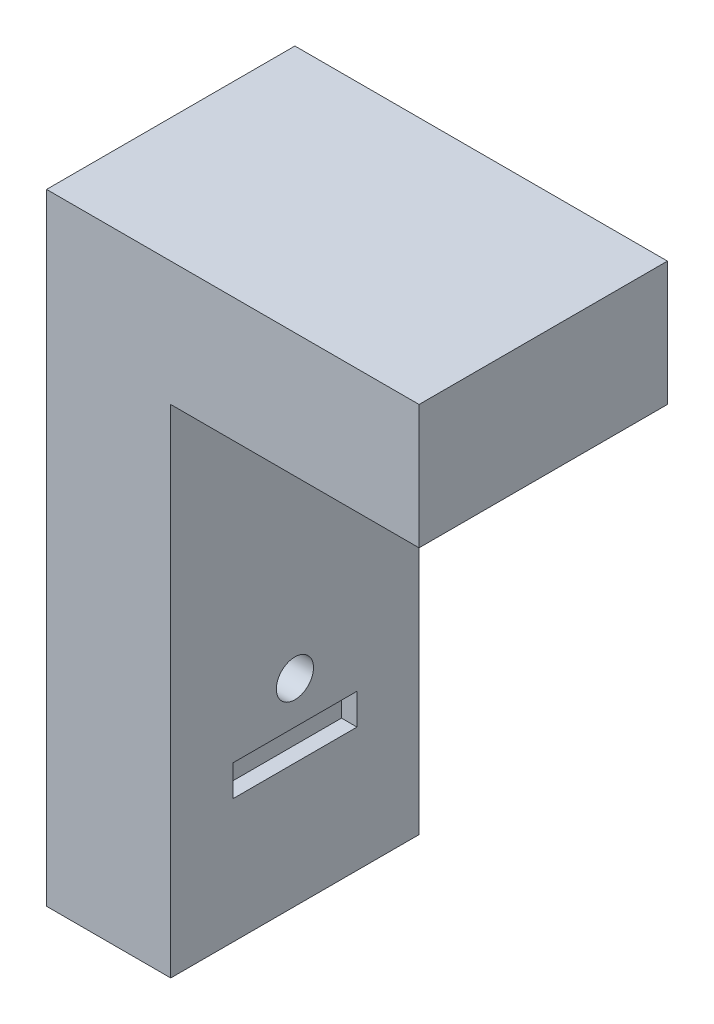
SolidWorks part; units mm, degrees
ref_plane "Front Plane" through (0, 0, 0) normal (0, 0, 1) x (1, 0, 0)
ref_plane "Top Plane" through (0, 0, 0) normal (0, 1, 0) x (1, 0, 0)
ref_plane "Right Plane" through (0, 0, 0) normal (1, 0, 0) x (0, 0, -1)
sketch "Sketch1" plane through (0, 0, 0) normal (0, 0, 1) x (1, 0, 0)
  line L0 (-12.7, 0) -> (-12.7, 63.5)
  line L1 (-12.7, 63.5) -> (25.4, 63.5)
  line L2 (25.4, 63.5) -> (25.4, 50.8)
  line L3 (25.4, 50.8) -> (0, 50.8)
  line L4 (0, 50.8) -> (0, 0)
  line L5 (0, 0) -> (-12.7, 0)
  dimension "D1" = 12.7
  dimension "D2" = 12.7
  dimension "D3" = 38.1
  dimension "D4" = 63.5
extrude "Boss-Extrude1" add sketch "Sketch1" against normal blind 25.4
sketch "Sketch2" plane through (0, 0, 0) normal (1, 0, 0) x (0, 0, -1)
  line L0 (25.4, 0) -> (0, 0) construction
  line L1 (6.35, 12.7) -> (19.05, 12.7)
  line L2 (6.35, 12.7) -> (6.35, 15.875)
  line L3 (6.35, 15.875) -> (19.05, 15.875)
  line L4 (19.05, 12.7) -> (19.05, 15.875)
  line L5 (25.4, 0) -> (25.4, 50.8) construction
  line L6 (0, 0) -> (0, 50.8) construction
  dimension "D1" = 12.7
  dimension "D2" = 6.35
  dimension "D3" = 6.35
  dimension "D4" = 3.175
extrude "Cut-Extrude1" cut sketch "Sketch2" against normal blind 1.5875
hole_wizard "CSK for #6 Flat Head Machine Screw (100)1" positions "Sketch5" profile "Sketch6" countersink size "#6" standard "ANSI Inch"
sketch "Sketch5" plane through (-12.7, -5.1507, -61.1192) normal (-1, 0, 0) x (0, 0, 1)
  point P0 (48.4192, 25.3448)
sketch "Sketch6" plane through (-12.7, 20.1942, -12.7) normal (0, 1, 0) x (0, 0, 1)
  line L0 (0, 0) -> (0, 26.5408)
  line L1 (0, 26.5408) -> (1.8986, 25.4)
  line L2 (1.8986, 25.4) -> (1.8986, 1.38)
  line L3 (1.8986, 1.38) -> (3.5433, 0)
  line L4 (3.5433, 0) -> (0, 0)
  line L5 (-1.8986, 1.38) -> (-3.5433, 0) construction
  line L6 (0, 26.5408) -> (-1.8987, 25.4) construction
  line L7 (0, -6.35) -> (0, 107.95) construction
  dimension "Hole Dia." = 3.7973
  dimension "Hole Depth" = 25.4
  dimension "Near C'Sink Dia." = 7.0866
  dimension "Near C'Sink Angle" = 100
  dimension "Drill Angle" = 118
